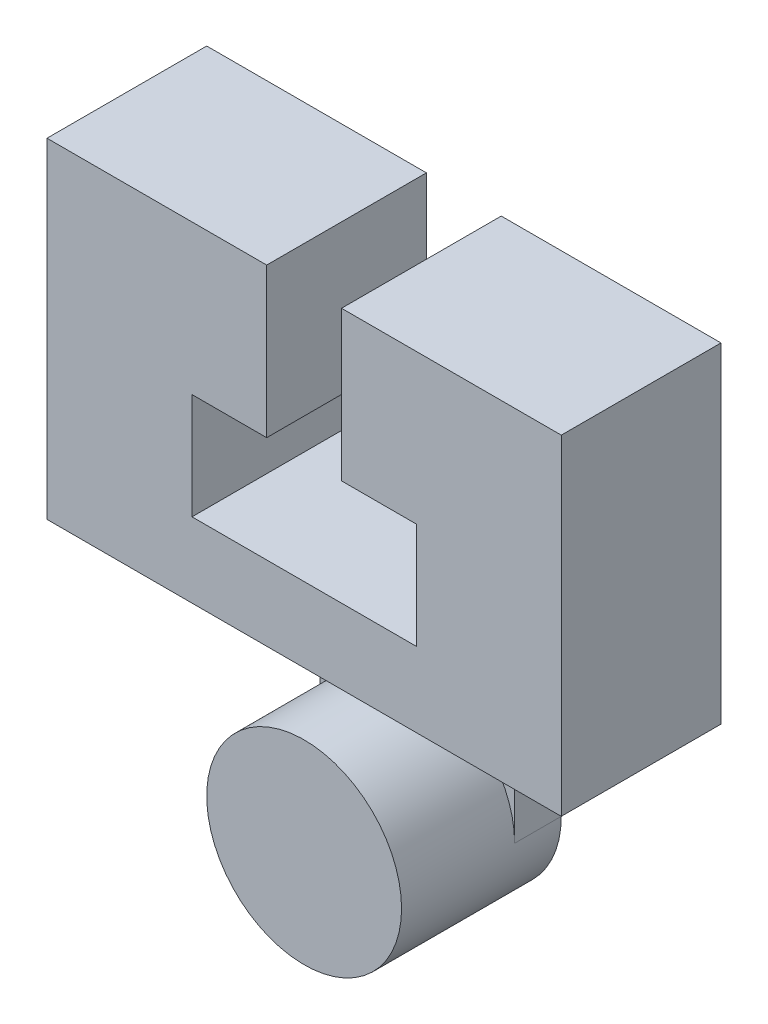
SolidWorks part; units mm, degrees
material "ASTM A36 Steel"
ref_plane "Front Plane" through (0, 0, 0) normal (0, 0, 1) x (1, 0, 0)
ref_plane "Top Plane" through (0, 0, 0) normal (0, 1, 0) x (1, 0, 0)
ref_plane "Right Plane" through (0, 0, 0) normal (1, 0, 0) x (0, 0, -1)
sketch "Sketch1" plane through (0, 0, 0) normal (0, 0, 1) x (1, 0, 0)
  circle A0 centre (0, 0) radius 15.494
  dimension "D1" = 30.988
extrude "Boss-Extrude1" add sketch "Sketch1" against normal blind 25.4
sketch "Sketch2" plane through (0, 0, -25.4) normal (0, 0, -1) x (-1, 0, 0)
  line L1 (-15.494, 0) -> (-15.494, 25.4)
  line L2 (-15.494, 25.4) -> (15.494, 25.4)
  line L3 (15.494, 25.4) -> (15.494, 0)
  circle A0 centre (0, 0) radius 15.494 construction
  arc A1 (15.494, 0) -> (-15.494, 0) centre (0, 0) ccw
  dimension "D1" = 25.4
  dimension "D2" = 30.988
extrude "Boss-Extrude2" add sketch "Sketch2" against normal blind 7.4168
sketch "Sketch3" plane through (0, 0, -25.4) normal (0, 0, -1) x (-1, 0, 0)
  line L0 (-15.494, 25.4) -> (-40.894, 25.4)
  line L1 (-40.894, 25.4) -> (-40.894, 77.9018)
  line L2 (-40.894, 77.9018) -> (40.894, 77.9018)
  line L3 (40.894, 77.9018) -> (40.894, 25.4)
  line L4 (40.894, 25.4) -> (15.494, 25.4)
  line L5 (15.494, 25.4) -> (-15.494, 25.4) construction
  line L6 (-15.494, 25.4) -> (15.494, 25.4)
  dimension "D1" = 25.4
  dimension "D2" = 25.4
  dimension "D3" = 52.5018
extrude "Boss-Extrude4" add sketch "Sketch3" against normal up to surface (25.4 mm away) up to face at (15.494, 0, 0)
sketch "Sketch4" plane through (0, 0, -25.4) normal (0, 0, -1) x (-1, 0, 0)
  line L0 (-5.9448, 77.9018) -> (-5.9448, 54.1274)
  line L1 (40.894, 77.9018) -> (-40.894, 77.9018) construction
  line L2 (-5.9448, 54.1274) -> (-17.8308, 54.1274)
  line L3 (-17.8308, 54.1274) -> (-17.8308, 37.2872)
  line L4 (-17.8308, 37.2872) -> (17.8308, 37.2872)
  line L5 (17.8308, 37.2872) -> (17.8308, 54.1274)
  line L6 (17.8308, 54.1274) -> (5.9555, 54.1274)
  line L7 (5.9555, 54.1274) -> (5.9555, 77.9018)
  line L8 (5.9555, 77.9018) -> (-5.9448, 77.9018)
  line L9 (-40.894, 25.4) -> (-15.494, 25.4) construction
  point P14 (0, 37.2872)
  dimension "D1" = 16.8402
  dimension "D2" = 11.8872
  dimension "D3" = 35.6616
  dimension "D4" = 11.886
  dimension "D5" = 11.8753
extrude "Cut-Extrude1" cut sketch "Sketch4" against normal through all
equation "\"L\"= 1'Length"
equation "\"A\"= 1.22'A Diameter"
equation "\"B\"= 0.146'Thickness/Height"
equation "\"C\"= 0.468'Thickness/Height"
equation "\"D\"= 0.663'Thickness/Height"
equation "\"E\"= 0.936'Thickness/Height"
equation "\"D1@Sketch1\"=\"A\""
equation "\"D1@Boss-Extrude1\"=\"L\""
equation "\"D1@Sketch2\"=\"L\""
equation "\"D2@Sketch2\"=\"A\""
equation "\"D1@Boss-Extrude2\"=\"B\"*2"
equation "\"D1@Sketch3\"=\"L\""
equation "\"D2@Sketch3\"=\"L\""
equation "\"D3@Sketch3\"=\"C\"+\"D\"+\"E\""
equation "\"D1@Sketch4\"=\"D\""
equation "\"D2@Sketch4\"=\"C\""
equation "\"BC\"= \"C\" * 3'C Length"
equation "\"D3@Sketch4\"=\"BC\""
equation "\"D4@Sketch4\"=\"BC\"*.3333"
equation "\"D5@Sketch4\"=\"BC\"*.333"
